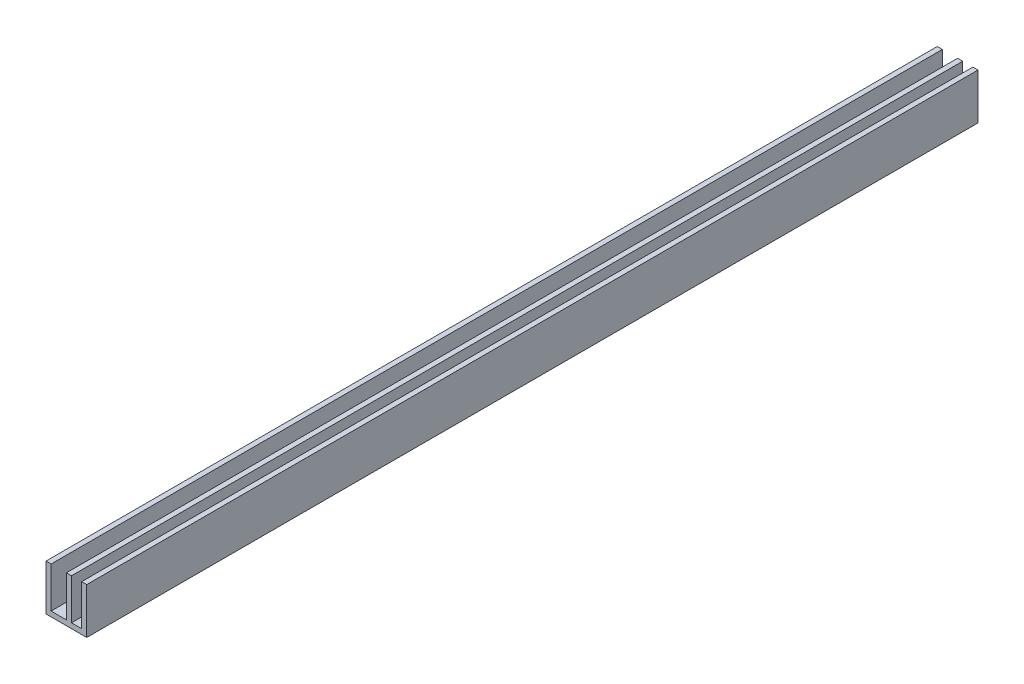
SolidWorks part; units mm, degrees
ref_plane "Alzado" through (0, 0, 0) normal (0, 0, 1) x (1, 0, 0)
ref_plane "Planta" through (0, 0, 0) normal (0, 1, 0) x (1, 0, 0)
ref_plane "Vista lateral" through (0, 0, 0) normal (1, 0, 0) x (0, 0, -1)
sketch "Croquis1" plane through (0, 0, 0) normal (0, 0, 1) x (1, 0, 0)
  line L0 (0, 0) -> (-800, 0)
  line L1 (-800, 0) -> (-800, 600)
  line L2 (-800, 600) -> (-700, 600)
  line L3 (-700, 600) -> (-700, 100)
  line L4 (-700, 100) -> (-400, 100)
  line L5 (-400, 100) -> (-400, 470)
  line L6 (-400, 470) -> (-300, 470)
  line L7 (-300, 470) -> (-300, 100)
  line L8 (-300, 100) -> (-100, 100)
  line L9 (-100, 100) -> (-100, 600)
  line L10 (-100, 600) -> (0, 600)
  line L11 (0, 600) -> (0, 0)
  dimension "D1" = 800
  dimension "D2" = 600
  dimension "D3" = 100
  dimension "D4" = 500
  dimension "D5" = 300
  dimension "D6" = 370
  dimension "D7" = 100
  dimension "D8" = 370
  dimension "D9" = 200
extrude "Saliente-Extruir1" add sketch "Croquis1" along normal blind 17500
sketch "Croquis2" plane through (0, 0, 0) normal (0, 0, -1) x (-1, 0, 0)
  line L0 (0, 600) -> (0, 900)
  line L1 (0, 900) -> (100, 900)
  line L2 (800, 900) -> (800, 600)
  line L3 (800, 600) -> (700, 600)
  line L4 (400, 600) -> (400, 470)
  line L5 (400, 470) -> (300, 470)
  line L6 (300, 900) -> (400, 900)
  line L8 (700, 900) -> (800, 900)
  line L9 (100, 600) -> (0, 600)
  line L10 (100, 600) -> (100, 900)
  line L11 (300, 470) -> (300, 900)
  line L12 (400, 600) -> (400, 900)
  line L13 (700, 600) -> (700, 900)
  dimension "D1" = 300
extrude "Saliente-Extruir2" add sketch "Croquis2" against normal up to surface (17500 mm away) up to face at (-383.3333, 311.6667, 17500)
